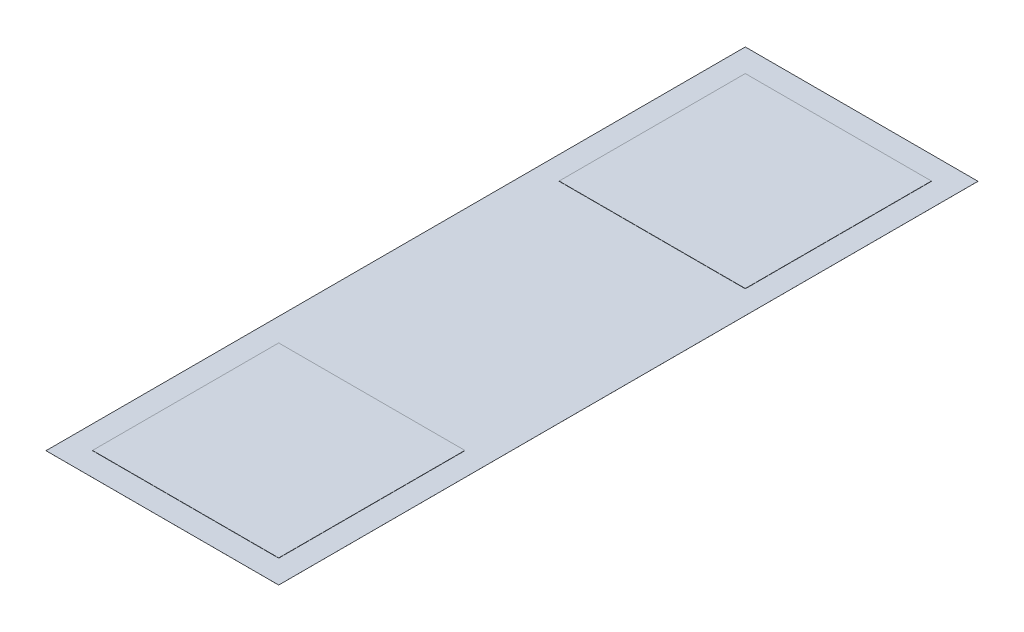
SolidWorks part; units mm, degrees
ref_plane "Front Plane" through (0, 0, 0) normal (0, 0, 1) x (1, 0, 0)
ref_plane "Top Plane" through (0, 0, 0) normal (0, 1, 0) x (1, 0, 0)
ref_plane "Right Plane" through (0, 0, 0) normal (1, 0, 0) x (0, 0, -1)
sketch "Sketch1" plane through (0, 0, 0) normal (0, 1, 0) x (1, 0, 0)
  line L1 (-50, 150.255) -> (50, 150.255)
  line L2 (-50, 150.255) -> (-50, -150.255)
  line L3 (-50, -150.255) -> (50, -150.255)
  line L4 (50, 150.255) -> (50, -150.255)
  line L5 (-50, 150.255) -> (50, -150.255) construction
  line L6 (-50, -150.255) -> (50, 150.255) construction
  point P0 (0, 0)
  dimension "D1" = 300.51
  dimension "D2" = 100
extrude "Boss-Extrude1" add sketch "Sketch1" along normal blind 0.01
sketch "Sketch2" plane through (0, 0.01, 0) normal (0, 1, 0) x (1, 0, 0)
  line L0 (-50, -150.255) -> (50, -150.255) construction
  line L1 (-40, -140.255) -> (40, -140.255)
  line L2 (-40, -140.255) -> (-40, -60.255)
  line L3 (-40, -60.255) -> (40, -60.255)
  line L4 (40, -140.255) -> (40, -60.255)
  line L5 (-50, 150.255) -> (-50, -150.255) construction
  line L6 (50, 150.255) -> (-50, 150.255) construction
  line L7 (-40, 140.255) -> (40, 140.255)
  line L8 (-40, 140.255) -> (-40, 60.255)
  line L9 (-40, 60.255) -> (40, 60.255)
  line L10 (40, 140.255) -> (40, 60.255)
  line L11 (50, -150.255) -> (50, 150.255) construction
  dimension "D1" = 10
  dimension "D2" = 10
  dimension "D3" = 80
  dimension "D4" = 80
  dimension "D5" = 10
  dimension "D6" = 80
  dimension "D7" = 80
  dimension "D8" = 10
  dimension "D9" = 120.51
  dimension "D10" = 10
extrude "Boss-Extrude2" add sketch "Sketch2" along normal blind 0.1
